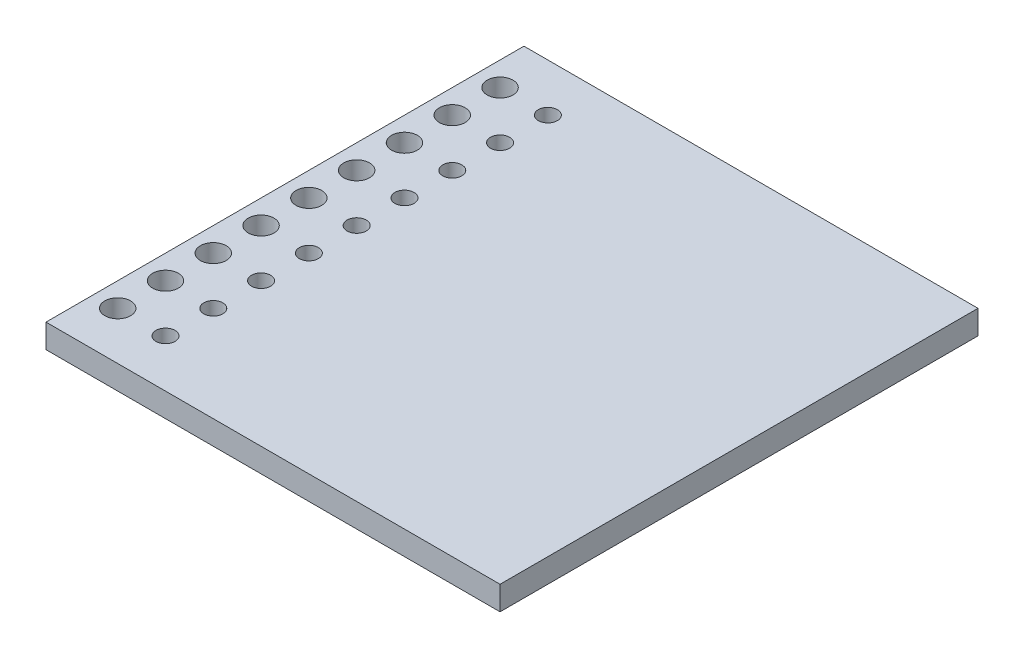
SolidWorks part; units mm, degrees
ref_plane "Front Plane" through (0, 0, 0) normal (0, 0, 1) x (1, 0, 0)
ref_plane "Top Plane" through (0, 0, 0) normal (0, 1, 0) x (1, 0, 0)
ref_plane "Right Plane" through (0, 0, 0) normal (1, 0, 0) x (0, 0, -1)
sketch "Sketch1" plane through (0, 0, 0) normal (0, 1, 0) x (1, 0, 0)
  line L1 (-50.8, -63.5) -> (50.8, -63.5)
  line L2 (-50.8, -63.5) -> (-50.8, 63.5)
  line L3 (-50.8, 63.5) -> (50.8, 63.5)
  line L4 (50.8, -63.5) -> (50.8, 63.5)
  line L5 (-50.8, -63.5) -> (50.8, 63.5) construction
  line L6 (-50.8, 63.5) -> (50.8, -63.5) construction
  line L11 (-41.275, -53.975) -> (41.275, 53.975) construction
  line L12 (-41.275, 53.975) -> (41.275, -53.975) construction
  point P0 (0, 0)
  point P5 (0, 0)
  dimension "D1" = 101.6
  dimension "D2" = 127
extrude "Boss-Extrude1" add sketch "Sketch1" along normal blind 6.35
sketch "Sketch3" plane through (0, 6.35, 0) normal (0, 1, 0) x (1, 0, 0)
  line L1 (-50.8, 63.5) -> (-114.3, 63.5)
  line L2 (-50.8, 63.5) -> (-50.8, -63.5)
  line L3 (-50.8, -63.5) -> (-114.3, -63.5)
  line L4 (-114.3, 63.5) -> (-114.3, -63.5)
  line L5 (-50.8, -63.5) -> (50.8, -63.5) construction
  circle A0 centre (-101.6, 50.8) radius 3.429
  circle A1 centre (-88.9, 50.8) radius 3.429
  circle A2 centre (-88.9, 38.1) radius 3.429
  circle A6 centre (-101.6, 38.1) radius 3.429
  circle A10 centre (-101.6, 25.4) radius 3.429
  circle A11 centre (-88.9, 25.4) radius 3.429
  circle A12 centre (-76.2, 50.8) radius 3.429
  circle A13 centre (-63.5, 50.8) radius 3.429
  circle A14 centre (-76.2, 38.1) radius 3.429
  circle A15 centre (-63.5, 38.1) radius 3.429
  circle A16 centre (-76.2, 25.4) radius 3.429
  circle A17 centre (-63.5, 25.4) radius 3.429
  circle A18 centre (-101.6, 12.7) radius 3.429
  circle A19 centre (-88.9, 12.7) radius 3.429
  circle A20 centre (-76.2, 12.7) radius 3.429
  circle A21 centre (-63.5, 12.7) radius 3.429
  circle A22 centre (-101.6, 0) radius 3.429
  circle A23 centre (-88.9, 0) radius 3.429
  circle A24 centre (-76.2, 0) radius 3.429
  circle A25 centre (-63.5, 0) radius 3.429
  circle A26 centre (-101.6, -12.7) radius 3.429
  circle A27 centre (-88.9, -12.7) radius 3.429
  circle A28 centre (-76.2, -12.7) radius 3.429
  circle A29 centre (-63.5, -12.7) radius 3.429
  circle A30 centre (-101.6, -25.4) radius 3.429
  circle A31 centre (-88.9, -25.4) radius 3.429
  circle A32 centre (-76.2, -25.4) radius 3.429
  circle A33 centre (-63.5, -25.4) radius 3.429
  circle A34 centre (-101.6, -38.1) radius 3.429
  circle A35 centre (-88.9, -38.1) radius 3.429
  circle A36 centre (-76.2, -38.1) radius 3.429
  circle A37 centre (-63.5, -38.1) radius 3.429
  circle A38 centre (-101.6, -50.8) radius 3.429
  circle A39 centre (-88.9, -50.8) radius 3.429
  circle A40 centre (-76.2, -50.8) radius 3.429
  circle A41 centre (-63.5, -50.8) radius 3.429
  dimension "D2" = 6.858
  dimension "D4" = 12.7
  dimension "D1" = 63.5
  dimension "D3" = 38.1
  dimension "D7" = 12.7
  dimension "D8" = 12.7
  dimension "D5" = 4
  dimension "D6" = 9
extrude "Boss-Extrude2" add sketch "Sketch3" against normal blind 6.35
sketch "Sketch4" plane through (0, 6.35, 0) normal (0, 1, 0) x (1, 0, 0)
  line L0 (-114.3, -63.5) -> (50.8, -63.5) construction
  line L1 (-69.85, -63.5) -> (-114.3, -63.5)
  line L2 (-69.85, -63.5) -> (-69.85, 63.5)
  line L3 (-69.85, 63.5) -> (-114.3, 63.5)
  line L4 (-114.3, -63.5) -> (-114.3, 63.5)
  dimension "D1" = 44.45
extrude "Cut-Extrude2" cut sketch "Sketch4" against normal through all
sketch "Sketch5" plane through (0, 0, 0) normal (0, 1, 0) x (1, 0, 0)
  circle A0 centre (-50.8, 50.8) radius 2.54
  circle A2 centre (-50.8, 38.1) radius 2.54
  circle A3 centre (-50.8, 25.4) radius 2.54
  circle A4 centre (-50.8, 12.7) radius 2.54
  circle A5 centre (-50.8, 0) radius 2.54
  circle A6 centre (-50.8, -12.7) radius 2.54
  circle A7 centre (-50.8, -25.4) radius 2.54
  circle A8 centre (-50.8, -38.1) radius 2.54
  circle A9 centre (-50.8, -50.8) radius 2.54
  point P5 (-63.5, 50.8)
  dimension "D1" = 5.08
  dimension "D2" = 12.7
  dimension "D3" = 9
extrude "Cut-Extrude4" cut sketch "Sketch5" along normal through all
